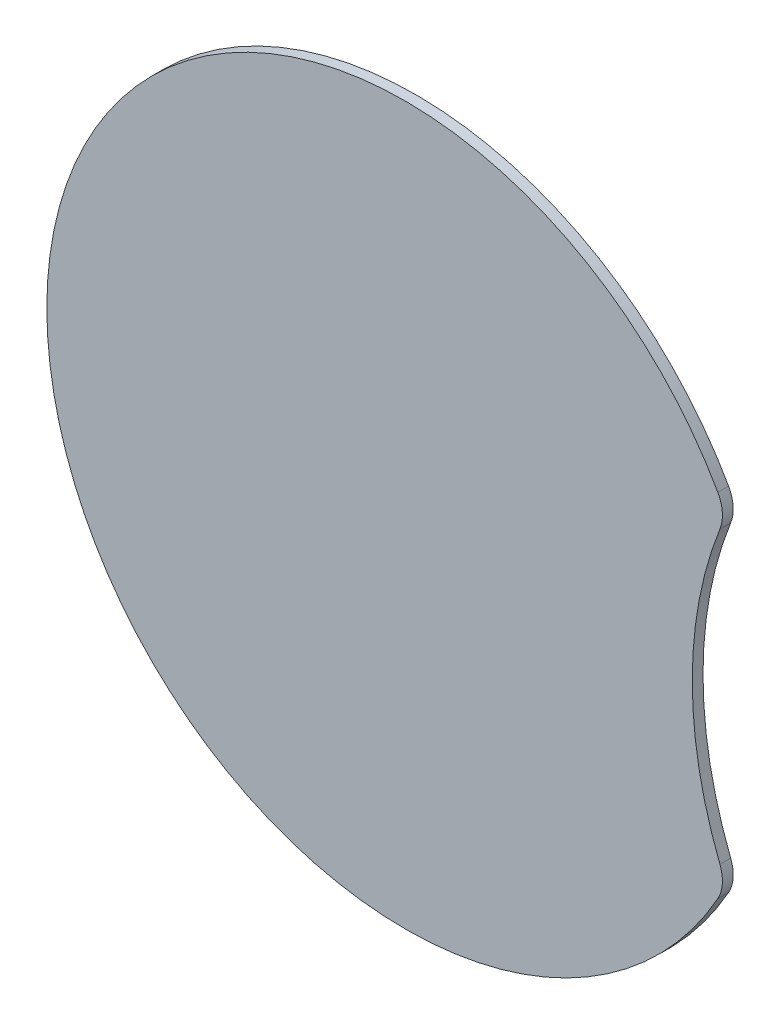
SolidWorks part; units mm, degrees
ref_plane "Alzado" through (0, 0, 0) normal (0, 0, 1) x (1, 0, 0)
ref_plane "Planta" through (0, 0, 0) normal (0, 1, 0) x (1, 0, 0)
ref_plane "Vista lateral" through (0, 0, 0) normal (1, 0, 0) x (0, 0, -1)
sketch "Croquis1" plane through (0, 0, 0) normal (0, 0, 1) x (1, 0, 0)
  circle A0 centre (0, 0) radius 100
  dimension "D1" = 200
extrude "Saliente-Extruir1" add sketch "Croquis1" along normal blind 3
sketch "Croquis3" plane through (0, 0, 3) normal (0, 0, 1) x (1, 0, 0)
  line L0 (0, 0) -> (190, 0) construction
  circle A0 centre (190, 0) radius 110
  dimension "D1" = 220
  dimension "D2" = 190
extrude "Cortar-Extruir1" cut sketch "Croquis3" against normal blind 3
fillet "Redondeo1" radius 10 2 edges at (89.4737, -44.6594, 1.5) (89.4737, 44.6594, 1.5)
